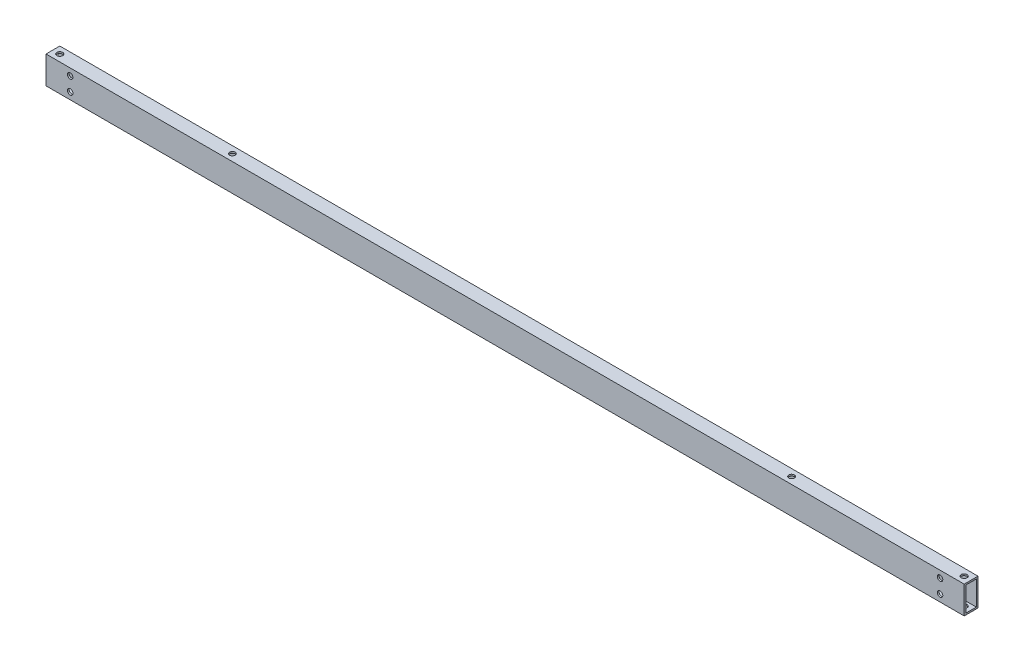
SolidWorks part; units mm, degrees
material "5052-H34"
ref_plane "正面" through (0, 0, 0) normal (0, 0, 1) x (1, 0, 0)
ref_plane "平面" through (0, 0, 0) normal (0, 1, 0) x (1, 0, 0)
ref_plane "右側面" through (0, 0, 0) normal (1, 0, 0) x (0, 0, -1)
sketch "ｽｹｯﾁ1" plane through (0, 0, 0) normal (1, 0, 0) x (0, 0, -1)
  line L1 (-5, 10) -> (5, 10)
  line L2 (-5, 10) -> (-5, -10)
  line L3 (-5, -10) -> (5, -10)
  line L4 (5, 10) -> (5, -10)
  line L5 (-5, 10) -> (5, -10) construction
  line L6 (-5, -10) -> (5, 10) construction
  point P0 (0, 0)
  dimension "D1" = 10
  dimension "D2" = 20
extrude "押し出し-薄板1" add sketch "ｽｹｯﾁ1" along normal blind 665 thin
sketch "ｽｹｯﾁ2" plane through (0, 0, 5) normal (0, 0, 1) x (1, 0, 0)
  line L0 (332.5, 10) -> (332.5, -10) construction
  line L1 (665, 10) -> (0, 10) construction
  line L2 (665, -10) -> (0, -10) construction
  line L3 (665, 0) -> (647.5, 0) construction
  line L4 (665, 10) -> (665, -10) construction
  line L5 (647.5, 0) -> (647.5, 5) construction
  line L7 (0, 0) -> (50000, 0) construction
  circle A0 centre (647.5, 5) radius 2
  circle A1 centre (647.5, -5) radius 2
  circle A2 centre (17.5, -5) radius 2
  circle A3 centre (17.5, 5) radius 2
  dimension "D1" = 4
  dimension "D2" = 17.5
  dimension "D3" = 10
extrude "ｶｯﾄ - 押し出し1" cut sketch "ｽｹｯﾁ2" against normal through all
sketch "ｽｹｯﾁ3" plane through (0, 10, 0) normal (0, 1, 0) x (1, 0, 0)
  line L0 (332.5, 5) -> (332.5, -5) construction
  line L1 (665, 5) -> (0, 5) construction
  line L2 (665, -5) -> (0, -5) construction
  line L3 (0, 0) -> (5, 0) construction
  line L4 (0, 5) -> (0, -5) construction
  circle A2 centre (130, 0) radius 2
  circle A3 centre (535, 0) radius 2
  circle A4 centre (5, 0) radius 2.1
  circle A5 centre (660, 0) radius 2.1
  dimension "D1" = 4.2
  dimension "D3" = 130
  dimension "D4" = 5
  dimension "D5" = 4
  dimension "D2" = 5
extrude "ｶｯﾄ - 押し出し2" cut sketch "ｽｹｯﾁ3" against normal through all
